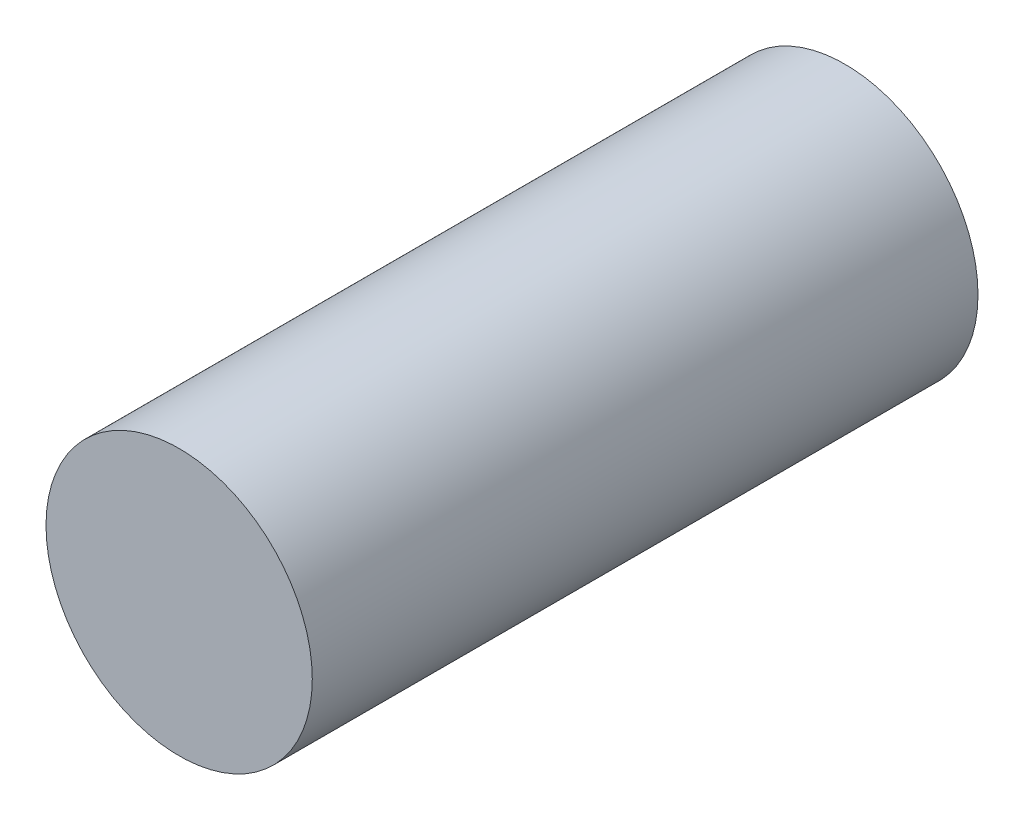
SolidWorks part; units mm, degrees
ref_plane "Front Plane" through (0, 0, 0) normal (0, 0, 1) x (1, 0, 0)
ref_plane "Top Plane" through (0, 0, 0) normal (0, 1, 0) x (1, 0, 0)
ref_plane "Right Plane" through (0, 0, 0) normal (1, 0, 0) x (0, 0, -1)
other "Configuration Table"
sketch "Sketch1" plane through (0, 0, 0) normal (0, 0, 1) x (1, 0, 0)
  circle A0 centre (460, 1744) radius 4
extrude "TOPPING_kat1_kapak_pimi_D8_2" add sketch "Sketch1" against normal blind 20 from offset 40 separate body
